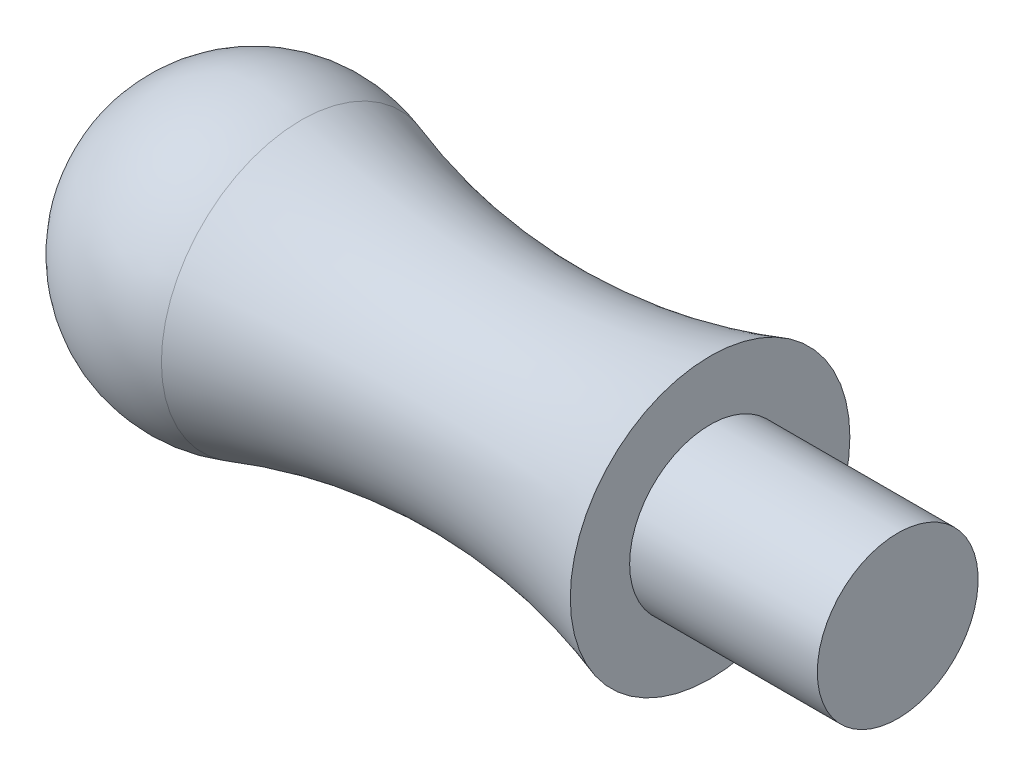
SolidWorks part; units mm, degrees
ref_plane "Front Plane" through (0, 0, 0) normal (0, 0, 1) x (1, 0, 0)
ref_plane "Top Plane" through (0, 0, 0) normal (0, 1, 0) x (1, 0, 0)
ref_plane "Right Plane" through (0, 0, 0) normal (1, 0, 0) x (0, 0, -1)
sketch "Sketch1" plane through (0, 0, 0) normal (0, 0, 1) x (1, 0, 0)
  line L0 (0, 0) -> (24, 0)
  line L1 (24, 0) -> (24, 3)
  line L2 (24, 3) -> (17, 3)
  line L3 (17, 3) -> (17, 5.2149)
  line L4 (0, 0) -> (-5.5, 0)
  arc A0 (1.7477, 5.2149) -> (-5.5, 0) centre (0, 0) ccw
  arc A1 (17, 5.2149) -> (1.7477, 5.2149) centre (9.3738, 27.9711) cw
  dimension "D4" = 5.5
  dimension "D5" = 24
  dimension "D1" = 3
  dimension "D2" = 24
  dimension "D3" = 7
revolve "Revolve2" add sketch "Sketch1" angle 360 about L0
cosmetic thread "Cosmetic Thread1" parameters "D1"=7, "D2"=4.891
